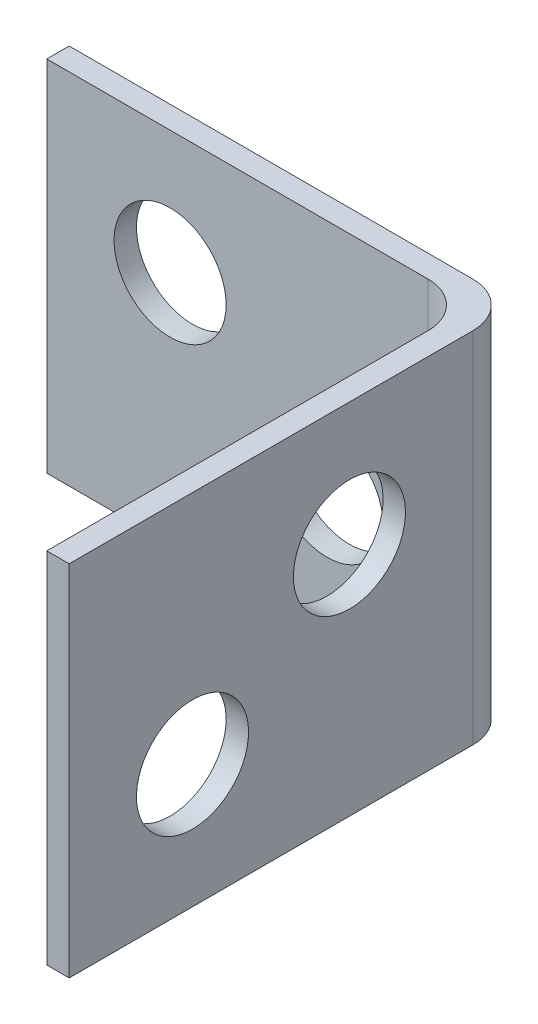
SolidWorks part; units mm, degrees
ref_plane "前视基准面" through (0, 0, 0) normal (0, 0, 1) x (1, 0, 0)
ref_plane "上视基准面" through (0, 0, 0) normal (0, 1, 0) x (1, 0, 0)
ref_plane "右视基准面" through (0, 0, 0) normal (1, 0, 0) x (0, 0, -1)
sketch "草图1" plane through (0, 0, 0) normal (0, 0, 1) x (1, 0, 0)
  line L1 (0, 0) -> (20, 0)
  line L2 (0, 0) -> (0, 16)
  line L3 (0, 16) -> (20, 16)
  line L4 (20, 0) -> (20, 16)
  circle A0 centre (5.5, 10.5) radius 2.5
  circle A1 centre (12.5, 5.5) radius 2.5
  dimension "D3" = 5
  dimension "D4" = 5
  dimension "D5" = 5.5
  dimension "D6" = 5.5
  dimension "D7" = 5.5
  dimension "D8" = 12.5
  dimension "D1" = 16
  dimension "D2" = 20
extrude "凸台-拉伸1" add sketch "草图1" along normal blind 1
sketch "草图2" plane through (0, 0, 1) normal (0, 0, 1) x (1, 0, 0)
  line L0 (0, 0) -> (20, 0) construction
  line L1 (20, 16) -> (19, 16)
  line L2 (20, 16) -> (20, 0)
  line L3 (20, 0) -> (19, 0)
  line L4 (19, 16) -> (19, 0)
  dimension "D1" = 1
extrude "凸台-拉伸2" add sketch "草图2" along normal blind 19
sketch "草图3" plane through (19, 0, 0) normal (-1, 0, 0) x (0, 0, 1)
  line L0 (20, 16) -> (20, 0) construction
  line L1 (20, 16) -> (1, 16) construction
  line L2 (20, 0) -> (1, 0) construction
  circle A0 centre (7.5, 10.5) radius 2.5
  circle A1 centre (14.5, 5.5) radius 2.5
  dimension "D1" = 12.5
  dimension "D2" = 5.5
  dimension "D3" = 5
  dimension "D4" = 5.5
  dimension "D5" = 5.5
  dimension "D6" = 5
extrude "切除-拉伸1" cut sketch "草图3" against normal through all
fillet "圆角2" radius 2 2 edges at (20, 8, 0) (19, 8, 1)
